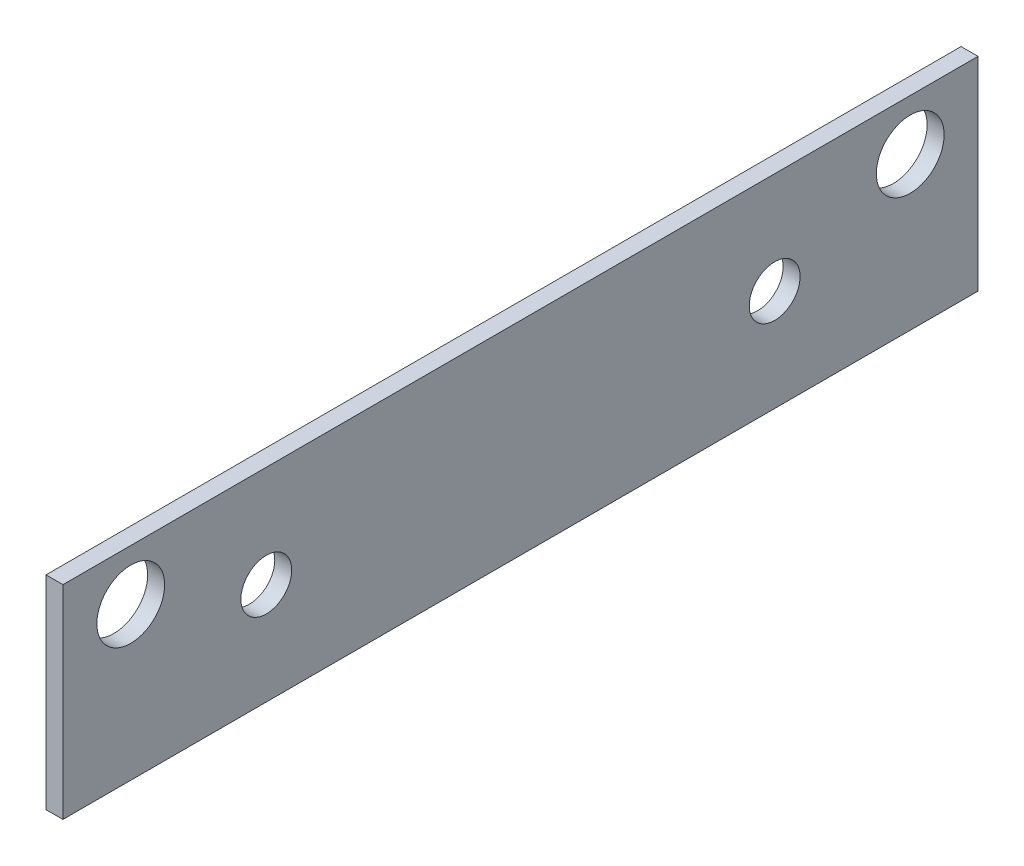
SolidWorks part; units mm, degrees
ref_plane "Front Plane" through (0, 0, 0) normal (0, 0, 1) x (1, 0, 0)
ref_plane "Top Plane" through (0, 0, 0) normal (0, 1, 0) x (1, 0, 0)
ref_plane "Right Plane" through (0, 0, 0) normal (1, 0, 0) x (0, 0, -1)
sketch "Sketch1" plane through (0, 0, 0) normal (0, 0, 1) x (1, 0, 0)
  line L1 (2.5, -30) -> (-2.5, -30)
  line L2 (2.5, -30) -> (2.5, 30)
  line L3 (2.5, 30) -> (-2.5, 30)
  line L4 (-2.5, -30) -> (-2.5, 30)
  line L5 (2.5, -30) -> (-2.5, 30) construction
  line L6 (2.5, 30) -> (-2.5, -30) construction
  point P0 (0, 0)
  dimension "D1" = 5
  dimension "D2" = 60
extrude "Boss-Extrude1" add sketch "Sketch1" along normal blind 270
sketch "Sketch2" plane through (2.5, 0, 0) normal (1, 0, 0) x (0, 0, -1)
  line L0 (-270, -30) -> (0, -30) construction
  line L1 (0, -30) -> (0, 30) construction
  line L2 (-270, -30) -> (-270, 30) construction
  line L3 (-270, 30) -> (0, 30) construction
  circle A0 centre (-60, 0) radius 7.5
  circle A1 centre (-210, 0) radius 7.5
  circle A2 centre (-250, 15) radius 10
  circle A3 centre (-20, 15) radius 10
  point P16 (-269.0837, 95.2773)
  point P17 (26.6237, 70.241)
  dimension "D2" = 15
  dimension "D3" = 15
  dimension "D11" = 20
  dimension "D12" = 20
  dimension "D1" = 150
  dimension "D4" = 30
  dimension "D5" = 30
  dimension "D6" = 60
  dimension "D7" = 20
  dimension "D8" = 20
  dimension "D9" = 15
  dimension "D10" = 15
extrude "Cut-Extrude1" cut sketch "Sketch2" against normal up to next
